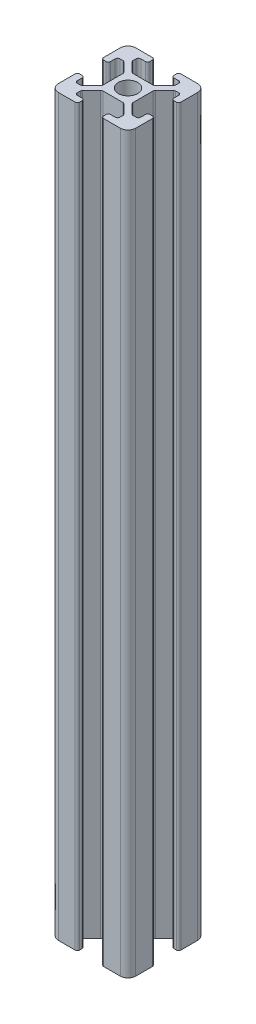
SolidWorks part; units mm, degrees
ref_plane "前视基准面" through (0, 0, 0) normal (0, 0, 1) x (1, 0, 0)
ref_plane "上视基准面" through (0, 0, 0) normal (0, 1, 0) x (1, 0, 0)
ref_plane "右视基准面" through (0, 0, 0) normal (1, 0, 0) x (0, 0, -1)
sketch "草图1" plane through (0, 0, 0) normal (0, 1, 0) x (1, 0, 0)
  line L0 (3.1, 8.8) -> (3.1, 9.4)
  line L1 (-10, -10) -> (10, -10) construction
  line L2 (-10, -10) -> (-10, 10) construction
  line L3 (-10, 10) -> (10, 10) construction
  line L4 (10, -10) -> (10, 10) construction
  line L5 (-10, -10) -> (10, 10) construction
  line L6 (-10, 10) -> (10, -10) construction
  line L7 (3.7, 10) -> (8, 10)
  line L8 (0, 10) -> (0, -10) construction
  line L9 (3.7, 8.2) -> (4.9, 8.2)
  line L10 (5.3243, 6.3849) -> (3.0151, 4.0757)
  line L11 (2.5908, 3.9) -> (0, 3.9)
  line L12 (5.5, 7.6) -> (5.5, 6.8092)
  line L13 (10, 3.7) -> (10, 8)
  line L14 (8.8, 3.1) -> (9.4, 3.1)
  line L15 (8.2, 3.7) -> (8.2, 4.9)
  line L16 (7.6, 5.5) -> (6.8092, 5.5)
  line L17 (6.3849, 5.3243) -> (4.0757, 3.0151)
  line L18 (3.9, 2.5908) -> (3.9, 0)
  line L19 (3.9, -2.5908) -> (3.9, 0)
  line L20 (2.5908, -3.9) -> (0, -3.9)
  line L21 (5.3243, -6.3849) -> (3.0151, -4.0757)
  line L22 (6.3849, -5.3243) -> (4.0757, -3.0151)
  line L23 (5.5, -7.6) -> (5.5, -6.8092)
  line L24 (3.7, -8.2) -> (4.9, -8.2)
  line L25 (3.1, -8.8) -> (3.1, -9.4)
  line L26 (3.7, -10) -> (8, -10)
  line L27 (10, -3.7) -> (10, -8)
  line L28 (8.8, -3.1) -> (9.4, -3.1)
  line L29 (8.2, -3.7) -> (8.2, -4.9)
  line L30 (7.6, -5.5) -> (6.8092, -5.5)
  line L31 (-2.5908, -3.9) -> (0, -3.9)
  line L32 (-3.9, -2.5908) -> (-3.9, 0)
  line L33 (-6.3849, -5.3243) -> (-4.0757, -3.0151)
  line L34 (-5.3243, -6.3849) -> (-3.0151, -4.0757)
  line L35 (-7.6, -5.5) -> (-6.8092, -5.5)
  line L36 (-8.2, -3.7) -> (-8.2, -4.9)
  line L37 (-8.8, -3.1) -> (-9.4, -3.1)
  line L38 (-10, -3.7) -> (-10, -8)
  line L39 (-3.7, -10) -> (-8, -10)
  line L40 (-3.1, -8.8) -> (-3.1, -9.4)
  line L41 (-3.7, -8.2) -> (-4.9, -8.2)
  line L42 (-5.5, -7.6) -> (-5.5, -6.8092)
  line L43 (-3.9, 2.5908) -> (-3.9, 0)
  line L44 (-2.5908, 3.9) -> (0, 3.9)
  line L45 (-5.3243, 6.3849) -> (-3.0151, 4.0757)
  line L46 (-6.3849, 5.3243) -> (-4.0757, 3.0151)
  line L47 (-5.5, 7.6) -> (-5.5, 6.8092)
  line L48 (-3.7, 8.2) -> (-4.9, 8.2)
  line L49 (-3.1, 8.8) -> (-3.1, 9.4)
  line L50 (-3.7, 10) -> (-8, 10)
  line L51 (-10, 3.7) -> (-10, 8)
  line L52 (-8.8, 3.1) -> (-9.4, 3.1)
  line L53 (-8.2, 3.7) -> (-8.2, 4.9)
  line L54 (-7.6, 5.5) -> (-6.8092, 5.5)
  circle A0 centre (0, 0) radius 2.5
  arc A1 (3.0151, 4.0757) -> (2.5908, 3.9) centre (2.5908, 4.5) cw
  arc A2 (5.5, 6.8092) -> (5.3243, 6.3849) centre (4.9, 6.8092) cw
  arc A3 (5.5, 7.6) -> (4.9, 8.2) centre (4.9, 7.6) ccw
  arc A4 (3.1, 8.8) -> (3.7, 8.2) centre (3.7, 8.8) ccw
  arc A5 (3.7, 10) -> (3.1, 9.4) centre (3.7, 9.4) ccw
  arc A6 (10, 3.7) -> (9.4, 3.1) centre (9.4, 3.7) cw
  arc A7 (8.8, 3.1) -> (8.2, 3.7) centre (8.8, 3.7) cw
  arc A8 (7.6, 5.5) -> (8.2, 4.9) centre (7.6, 4.9) cw
  arc A9 (6.8092, 5.5) -> (6.3849, 5.3243) centre (6.8092, 4.9) ccw
  arc A10 (4.0757, 3.0151) -> (3.9, 2.5908) centre (4.5, 2.5908) ccw
  arc A11 (10, 8) -> (8, 10) centre (8, 8) ccw
  arc A12 (3.0151, -4.0757) -> (2.5908, -3.9) centre (2.5908, -4.5) ccw
  arc A13 (4.0757, -3.0151) -> (3.9, -2.5908) centre (4.5, -2.5908) cw
  arc A14 (5.5, -6.8092) -> (5.3243, -6.3849) centre (4.9, -6.8092) ccw
  arc A15 (6.8092, -5.5) -> (6.3849, -5.3243) centre (6.8092, -4.9) cw
  arc A16 (5.5, -7.6) -> (4.9, -8.2) centre (4.9, -7.6) cw
  arc A17 (3.1, -8.8) -> (3.7, -8.2) centre (3.7, -8.8) cw
  arc A18 (3.7, -10) -> (3.1, -9.4) centre (3.7, -9.4) cw
  arc A19 (8, -10) -> (10, -8) centre (8, -8) ccw
  arc A20 (10, -3.7) -> (9.4, -3.1) centre (9.4, -3.7) ccw
  arc A21 (8.8, -3.1) -> (8.2, -3.7) centre (8.8, -3.7) ccw
  arc A22 (7.6, -5.5) -> (8.2, -4.9) centre (7.6, -4.9) ccw
  arc A23 (-4.0757, -3.0151) -> (-3.9, -2.5908) centre (-4.5, -2.5908) ccw
  arc A24 (-3.0151, -4.0757) -> (-2.5908, -3.9) centre (-2.5908, -4.5) cw
  arc A25 (-6.8092, -5.5) -> (-6.3849, -5.3243) centre (-6.8092, -4.9) ccw
  arc A26 (-5.5, -6.8092) -> (-5.3243, -6.3849) centre (-4.9, -6.8092) cw
  arc A27 (-7.6, -5.5) -> (-8.2, -4.9) centre (-7.6, -4.9) cw
  arc A28 (-8.8, -3.1) -> (-8.2, -3.7) centre (-8.8, -3.7) cw
  arc A29 (-10, -3.7) -> (-9.4, -3.1) centre (-9.4, -3.7) cw
  arc A30 (-10, -8) -> (-8, -10) centre (-8, -8) ccw
  arc A31 (-3.7, -10) -> (-3.1, -9.4) centre (-3.7, -9.4) ccw
  arc A32 (-3.1, -8.8) -> (-3.7, -8.2) centre (-3.7, -8.8) ccw
  arc A33 (-5.5, -7.6) -> (-4.9, -8.2) centre (-4.9, -7.6) ccw
  arc A34 (-3.0151, 4.0757) -> (-2.5908, 3.9) centre (-2.5908, 4.5) ccw
  arc A35 (-4.0757, 3.0151) -> (-3.9, 2.5908) centre (-4.5, 2.5908) cw
  arc A36 (-5.5, 6.8092) -> (-5.3243, 6.3849) centre (-4.9, 6.8092) ccw
  arc A37 (-6.8092, 5.5) -> (-6.3849, 5.3243) centre (-6.8092, 4.9) cw
  arc A38 (-5.5, 7.6) -> (-4.9, 8.2) centre (-4.9, 7.6) cw
  arc A39 (-3.1, 8.8) -> (-3.7, 8.2) centre (-3.7, 8.8) cw
  arc A40 (-3.7, 10) -> (-3.1, 9.4) centre (-3.7, 9.4) cw
  arc A41 (-8, 10) -> (-10, 8) centre (-8, 8) ccw
  arc A42 (-10, 3.7) -> (-9.4, 3.1) centre (-9.4, 3.7) ccw
  arc A43 (-8.8, 3.1) -> (-8.2, 3.7) centre (-8.8, 3.7) ccw
  arc A44 (-7.6, 5.5) -> (-8.2, 4.9) centre (-7.6, 4.9) ccw
  point P0 (0, 0)
  point P20 (5.5, 6.5607)
  point P25 (3.1, 8.2)
  point P28 (3.1, 10)
  point P156 (0, 0)
  dimension "D3" = 5
  dimension "D9" = 0.6
  dimension "D10" = 2
  dimension "D1" = 20
  dimension "D2" = 20
  dimension "D4" = 6.1
  dimension "D5" = 1.5
  dimension "D6" = 1.8
  dimension "D7" = 3.1
  dimension "D8" = 4.5
  dimension "D11" = 4
extrude "凸台-拉伸1" add sketch "草图1" along normal blind 190
